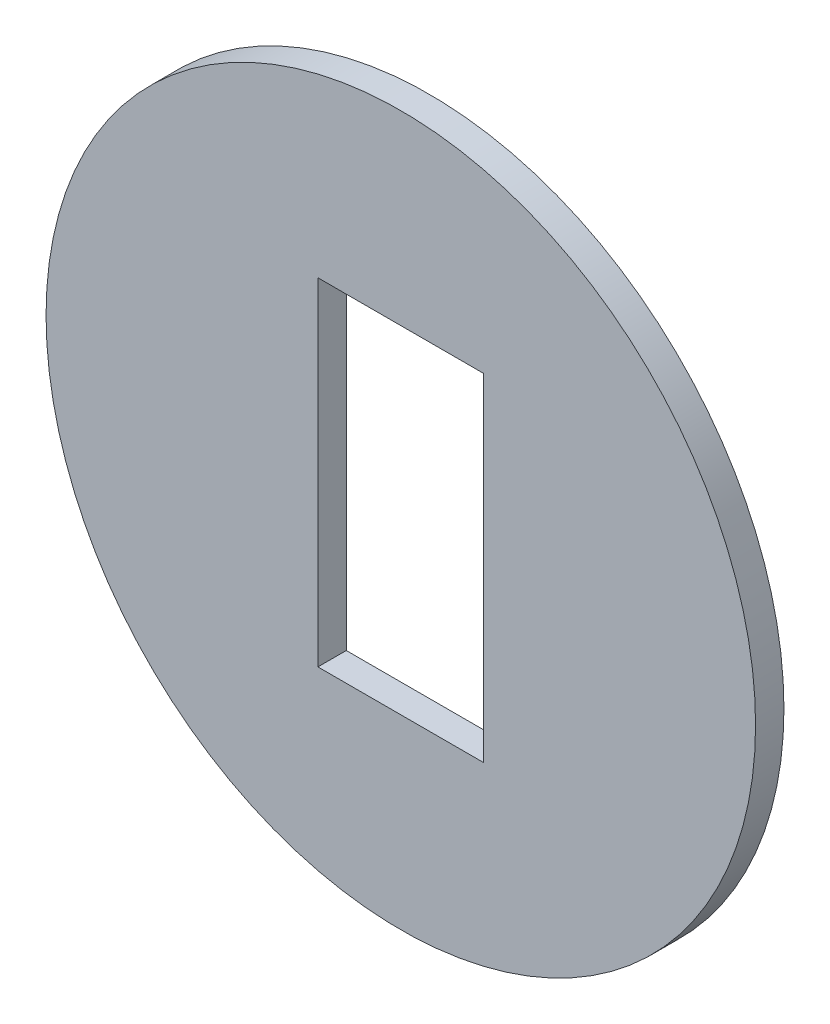
SolidWorks part; units mm, degrees
ref_plane "Plan de face" through (0, 0, 0) normal (0, 0, 1) x (1, 0, 0)
ref_plane "Plan de dessus" through (0, 0, 0) normal (0, 1, 0) x (1, 0, 0)
ref_plane "Plan de droite" through (0, 0, 0) normal (1, 0, 0) x (0, 0, -1)
sketch "Esquisse1" plane through (0, 0, 0) normal (0, 0, 1) x (1, 0, 0)
  circle A0 centre (0, 0) radius 25
  dimension "D1" = 50
extrude "Boss.-Extru.1" add sketch "Esquisse1" along normal blind 2
sketch "Esquisse2" plane through (0, 0, 2) normal (0, 0, 1) x (1, 0, 0)
  line L1 (5.842, 11.8745) -> (-5.842, 11.8745)
  line L2 (5.842, 11.8745) -> (5.842, -11.8745)
  line L3 (5.842, -11.8745) -> (-5.842, -11.8745)
  line L4 (-5.842, 11.8745) -> (-5.842, -11.8745)
  line L5 (5.842, 11.8745) -> (-5.842, -11.8745) construction
  line L6 (5.842, -11.8745) -> (-5.842, 11.8745) construction
  point P0 (0, 0)
  dimension "D1" = 23.749
  dimension "D2" = 11.684
extrude "Enlèv. mat.-Extru.1" cut sketch "Esquisse2" against normal up to next
